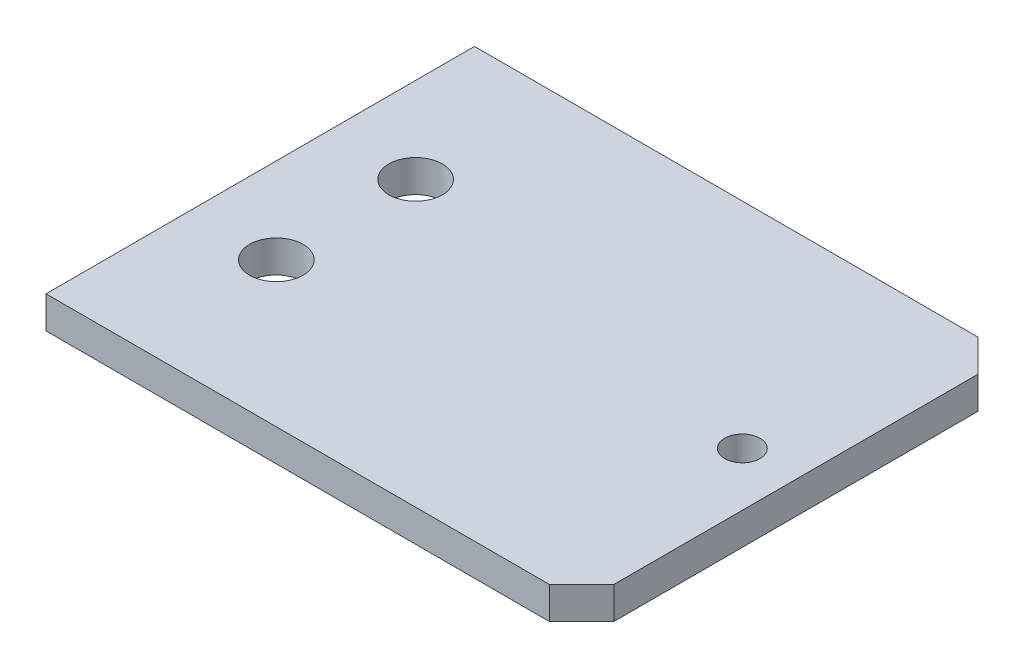
SolidWorks part; units mm, degrees
material "A5083"
ref_plane "Front Plane" through (0, 0, 0) normal (0, 0, 1) x (1, 0, 0)
ref_plane "Top Plane" through (0, 0, 0) normal (0, 1, 0) x (1, 0, 0)
ref_plane "Right Plane" through (0, 0, 0) normal (1, 0, 0) x (0, 0, -1)
sketch "Sketch1" plane through (0, 0, 0) normal (0, 1, 0) x (1, 0, 0)
  line L0 (47, 40) -> (50, 37)
  line L1 (0, 0) -> (47, 0)
  line L2 (0, 0) -> (0, 40)
  line L3 (0, 40) -> (47, 40)
  line L4 (50, 3) -> (50, 37)
  line L5 (47, 0) -> (50, 3)
  point P1 (50, 40)
  point P3 (50, 0)
  dimension "D1" = 40
  dimension "D2" = 50
extrude "Boss-Extrude1" add sketch "Sketch1" against normal blind 3
hole_wizard "M4x0.7 Tapped Hole1" positions "Sketch2" profile "Sketch3" tap size "M4x0.7" standard "JIS" end condition through all
sketch "Sketch2" plane through (0, 0, 0) normal (0, 1, 0) x (1, 0, 0)
  line L0 (50, 3) -> (50, 37) construction
  line L1 (0, 0) -> (47, 0) construction
  point P0 (45, 20)
  dimension "D1" = 5
  dimension "D2" = 20
sketch "Sketch3" plane through (45, 0, -20) normal (1, 0, 0) x (0, 0, 1)
  line L0 (0, 0) -> (0, 3)
  line L1 (0, 3) -> (1.65, 3)
  line L2 (1.65, 3) -> (1.65, 0)
  line L5 (1.65, 0) -> (0, 0)
  line L11 (0, -6.35) -> (0, 107.95) construction
  dimension "Thru Tap Drill Dia." = 3.3
  dimension "Thru Tap Drill Depth" = 3
cosmetic thread "Hole Thread1"
hole_wizard "M6x1.0 Tapped Hole2" positions "Sketch4" profile "Sketch5" tap size "M6x1.0" standard "JIS" end condition through all
sketch "Sketch4" plane through (0, 0, 0) normal (0, 1, 0) x (1, 0, 0)
  line L0 (0, 40) -> (0, 0) construction
  line L1 (0, 0) -> (47, 0) construction
  point P0 (8, 13.5)
  point P2 (8, 26.5)
  dimension "D1" = 8
  dimension "D2" = 13.5
  dimension "D3" = 13
sketch "Sketch5" plane through (8, 0, -13.5) normal (1, 0, 0) x (0, 0, 1)
  line L0 (0, 0) -> (0, 3)
  line L1 (0, 3) -> (2.5, 3)
  line L2 (2.5, 3) -> (2.5, 0)
  line L5 (2.5, 0) -> (0, 0)
  line L11 (0, -6.35) -> (0, 107.95) construction
  dimension "Thru Tap Drill Dia." = 5
  dimension "Thru Tap Drill Depth" = 3
cosmetic thread "Hole Thread2"
cosmetic thread "Hole Thread3"
